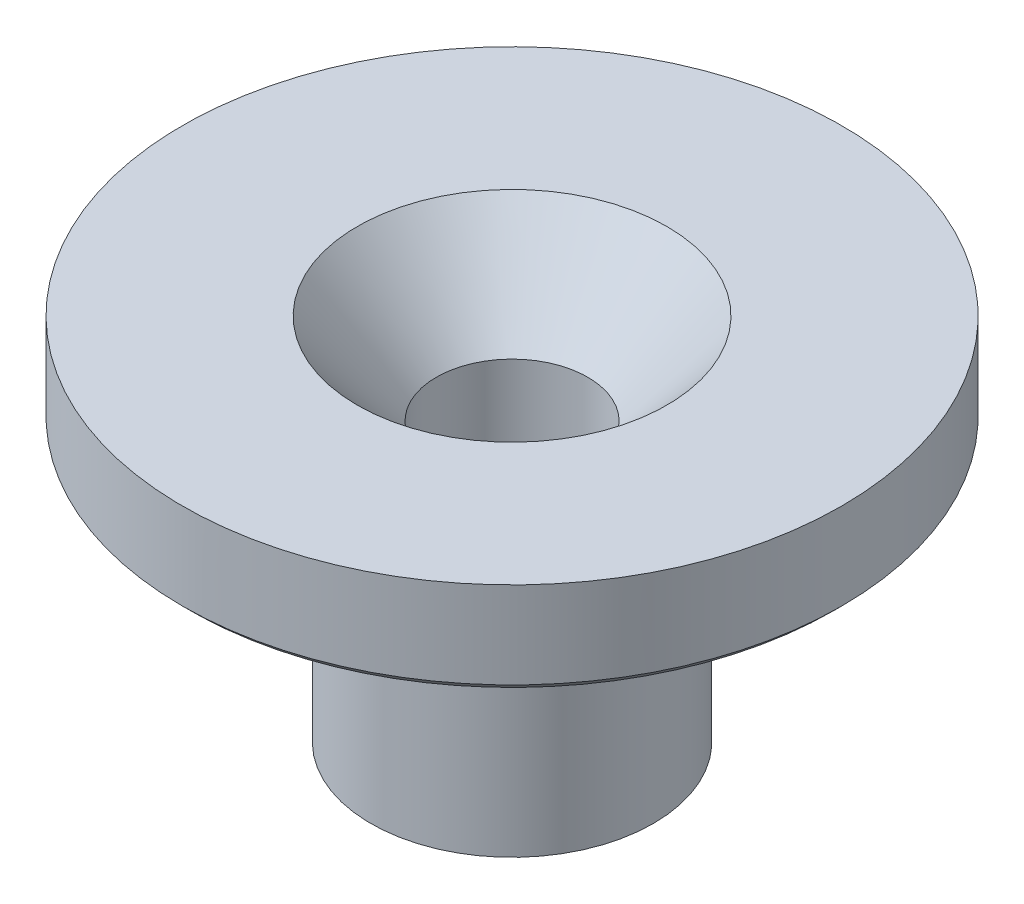
SolidWorks part; units mm, degrees
ref_plane "Front Plane" through (0, 0, 0) normal (0, 0, 1) x (1, 0, 0)
ref_plane "Top Plane" through (0, 0, 0) normal (0, 1, 0) x (1, 0, 0)
ref_plane "Right Plane" through (0, 0, 0) normal (1, 0, 0) x (0, 0, -1)
sketch "Sketch2" plane through (0, 0, 0) normal (0, 0, 1) x (1, 0, 0)
  line L0 (0, 10.1405) -> (-11.1125, 10.1405)
  line L1 (0, -55) -> (0, 55) construction
  line L2 (-11.1125, 10.1405) -> (-11.1125, 6.9655)
  line L3 (-11.1125, 6.9655) -> (-4.7625, 6.9655)
  line L4 (-4.7625, 6.9655) -> (-4.7625, -2.3055)
  line L5 (-4.7625, -2.3055) -> (0, -2.3055)
  line L6 (0, -2.3055) -> (0, 10.1405) construction
  line L7 (0, 10.1405) -> (0, -2.3055)
  point P8 (-2.3812, -2.3055)
  dimension "D1" = 9.271
  dimension "D2" = 11.1125
  dimension "D3" = 4.7625
  dimension "D4" = 3.175
revolve "Revolve1" add sketch "Sketch2" angle 360 about L6
hole_wizard "CSK for #10 Flat Head Socket Cap Screw1" positions "Sketch3" profile "Sketch4" countersink size "#10" standard "ANSI Inch" end condition through all
sketch "Sketch3" plane through (0, 10.1405, 0) normal (0, 1, 0) x (1, 0, 0)
  point P0 (0, 0)
sketch "Sketch4" plane through (0, 10.1405, 0) normal (1, 0, 0) x (0, 0, 1)
  line L0 (0, 0) -> (0, 12.446)
  line L1 (0, 12.446) -> (2.5527, 12.446)
  line L2 (2.5527, 12.446) -> (2.5527, 3.068)
  line L3 (2.5527, 3.068) -> (5.2197, 0)
  line L5 (5.2197, 0) -> (0, 0)
  line L6 (-2.5527, 3.068) -> (-5.2197, 0) construction
  line L11 (0, -6.35) -> (0, 107.95) construction
  dimension "Thru Hole Dia." = 5.1054
  dimension "Thru Hole Depth" = 12.446
  dimension "Near C'Sink Dia." = 10.4394
  dimension "Near C'Sink Angle" = 82
chamfer "Chamfer1" distance 0.254 angle 45 1 edges at (11.1125, 6.9655, 0)
